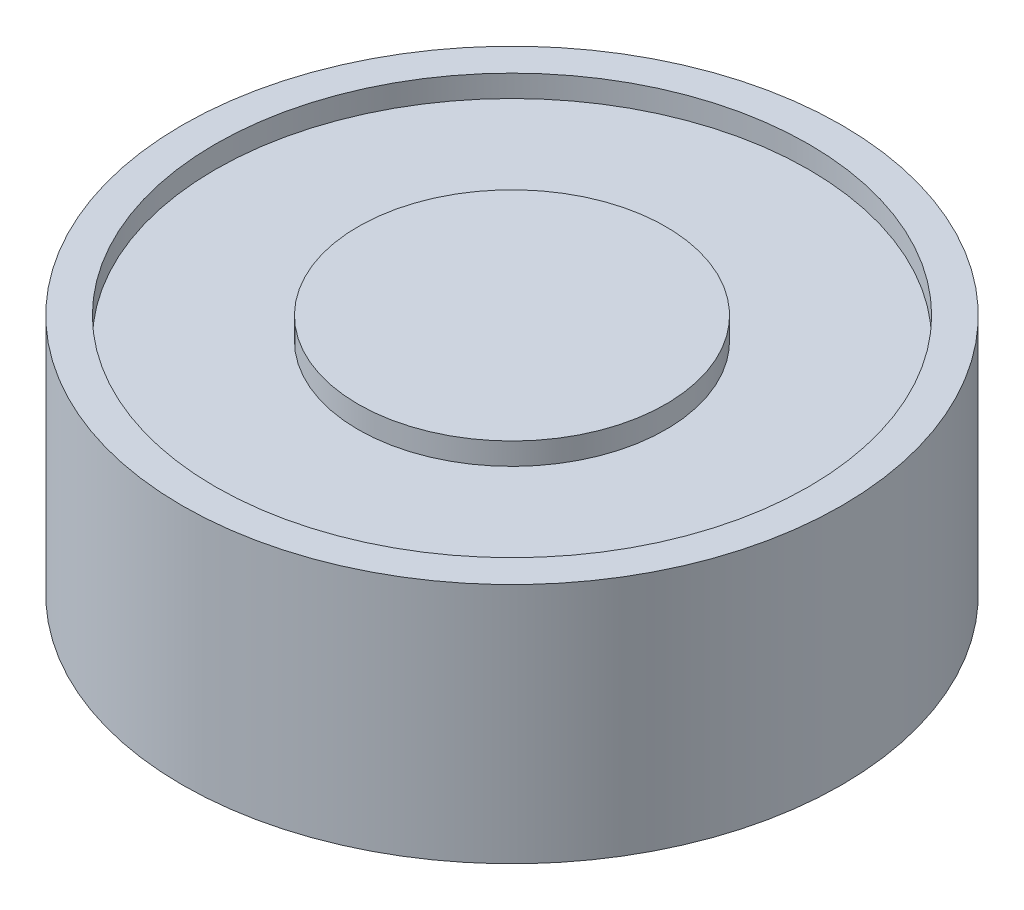
SolidWorks part; units mm, degrees
ref_plane "Front Plane" through (0, 0, 0) normal (0, 0, 1) x (1, 0, 0)
ref_plane "Top Plane" through (0, 0, 0) normal (0, 1, 0) x (1, 0, 0)
ref_plane "Right Plane" through (0, 0, 0) normal (1, 0, 0) x (0, 0, -1)
sketch "Sketch1" plane through (0, 0, 0) normal (0, 1, 0) x (1, 0, 0)
  circle A0 centre (0, 0) radius 30
extrude "Boss-Extrude1" add sketch "Sketch1" along normal blind 22
sketch "Sketch2" plane through (0, 22, 0) normal (0, 1, 0) x (1, 0, 0)
  circle A0 centre (0, 0) radius 27
extrude "Cut-Extrude1" cut sketch "Sketch2" against normal blind 2
sketch "Sketch3" plane through (0, 20, 0) normal (0, 1, 0) x (1, 0, 0)
  circle A0 centre (0, 0) radius 14
extrude "Boss-Extrude2" add sketch "Sketch3" along normal blind 2
hole_wizard "M3 Clearance Hole1" positions "Sketch4" profile "Sketch5" hole size "M3" standard "ANSI Metric"
sketch "Sketch4" plane through (0, 0, 0) normal (0, -1, 0) x (-1, 0, 0)
  point P0 (0, 0)
sketch "Sketch5" plane through (0, 0, 0) normal (1, 0, 0) x (0, 0, -1)
  line L0 (0, 0) -> (0, 8.0215)
  line L1 (0, 8.0215) -> (1.7, 7)
  line L2 (1.7, 7) -> (1.7, 0)
  line L5 (1.7, 0) -> (0, 0)
  line L10 (0, 8.0215) -> (-1.7, 7) construction
  line L11 (0, -6.35) -> (0, 107.95) construction
  dimension "Hole Dia." = 3.4
  dimension "Hole Depth" = 7
  dimension "Drill Angle" = 118
